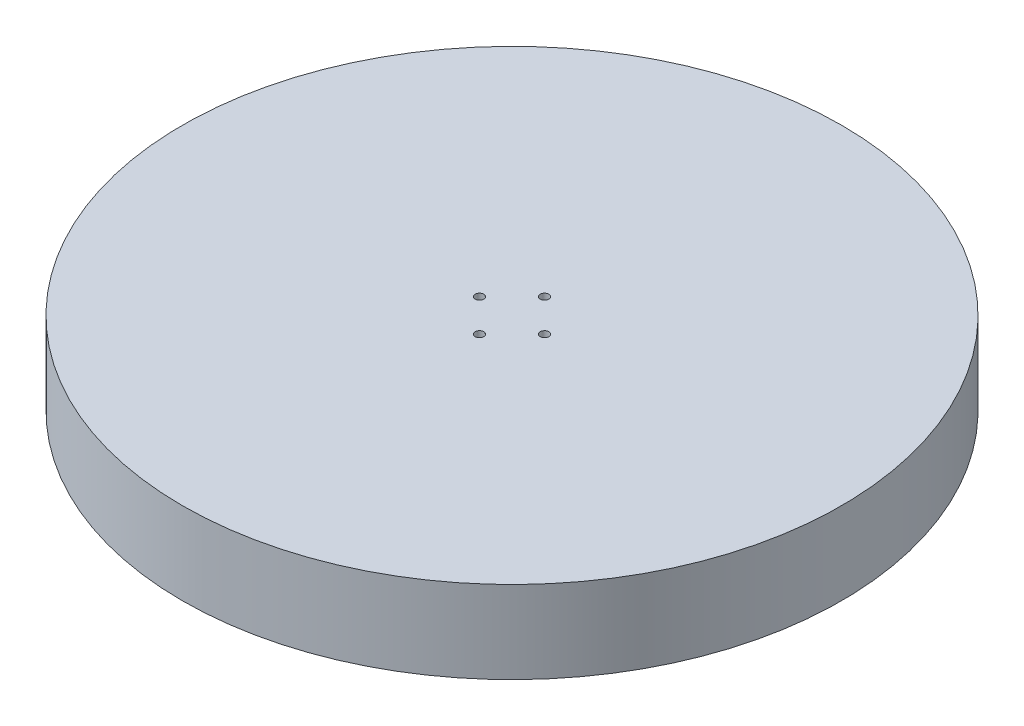
SolidWorks part; units mm, degrees
ref_plane "Front Plane" through (0, 0, 0) normal (0, 0, 1) x (1, 0, 0)
ref_plane "Top Plane" through (0, 0, 0) normal (0, 1, 0) x (1, 0, 0)
ref_plane "Right Plane" through (0, 0, 0) normal (1, 0, 0) x (0, 0, -1)
sketch "Sketch1" plane through (0, 0, 0) normal (0, 1, 0) x (1, 0, 0)
  circle A0 centre (0, 0) radius 150
  dimension "D1" = 300
extrude "Boss-Extrude1" add sketch "Sketch1" along normal blind 4
sketch "Sketch2" plane through (0, 4, 0) normal (0, 1, 0) x (1, 0, 0)
  circle A0 centre (0, 85.7383) radius 15
  circle A1 centre (85.7383, 0) radius 15
  circle A2 centre (0, -85.7383) radius 15
  circle A3 centre (-85.7383, 0) radius 15
  point P11 (0, 0)
  dimension "D1" = 30
  dimension "D2" = 4
extrude "Boss-Extrude2" add sketch "Sketch2" along normal blind 30
ref_plane "Plane1" through (0, 34, 0) normal (0, 1, 0) x (1, 0, 0)
sketch "Sketch3" plane through (0, 34, 0) normal (0, 1, 0) x (1, 0, 0)
  circle A0 centre (0, 0) radius 150
  dimension "D1" = 300
extrude "Boss-Extrude3" add sketch "Sketch3" along normal blind 4
sketch "Sketch5" plane through (0, 0, 0) normal (0, -1, 0) x (1, 0, 0)
  line L0 (0, 0) -> (0, 15) construction
  circle A0 centre (0, 15) radius 2
  circle A1 centre (15, 0) radius 2
  circle A2 centre (0, -15) radius 2
  circle A3 centre (-15, 0) radius 2
  point P13 (0, 0)
  dimension "D2" = 4
  dimension "D1" = 15
  dimension "D3" = 4
extrude "Cut-Extrude1" cut sketch "Sketch5" against normal blind 53
sketch "Sketch6" plane through (0, 0, 0) normal (1, 0, 0) x (0, 0, -1)
  line L1 (-150, 0) -> (-152, 0)
  line L2 (-150, 0) -> (-150, 38)
  line L3 (-150, 38) -> (-152, 38)
  line L4 (-152, 0) -> (-152, 38)
  dimension "D1" = 38
  dimension "D2" = 2
sweep "Sweep2" add profiles "Sketch6" path edge at (0, 38, 150)
